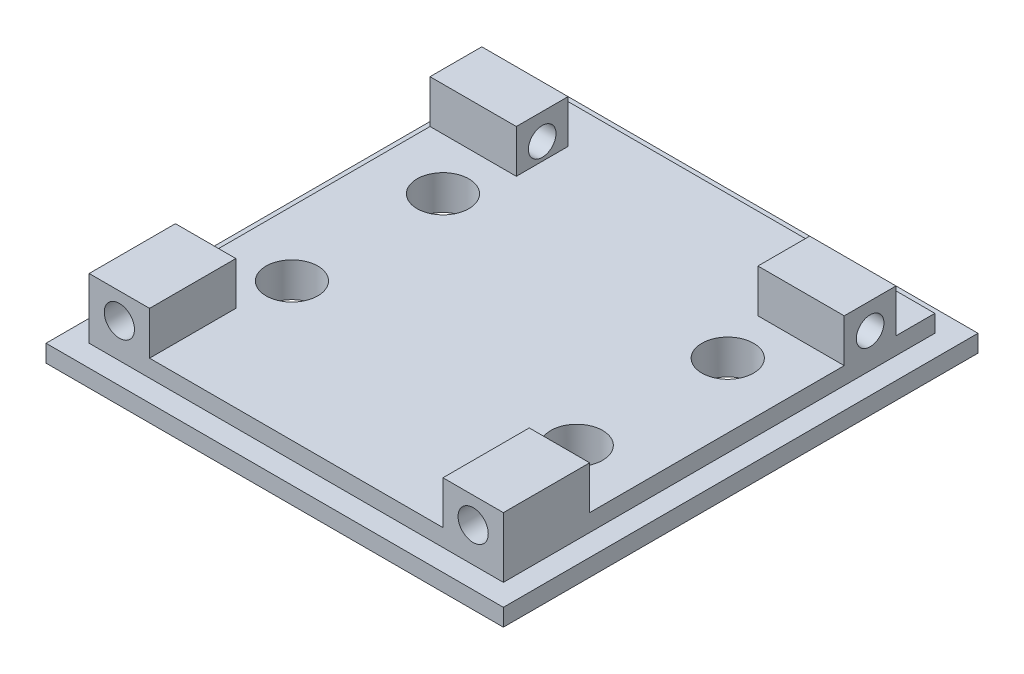
SolidWorks part; units mm, degrees
ref_plane "Front Plane" through (0, 0, 0) normal (0, 0, 1) x (1, 0, 0)
ref_plane "Top Plane" through (0, 0, 0) normal (0, 1, 0) x (1, 0, 0)
ref_plane "Right Plane" through (0, 0, 0) normal (1, 0, 0) x (0, 0, -1)
sketch "Sketch1" plane through (0, 0, 0) normal (0, 1, 0) x (1, 0, 0)
  line L1 (26.5, -27.5) -> (-26.5, -27.5)
  line L2 (26.5, -27.5) -> (26.5, 27.5)
  line L3 (26.5, 27.5) -> (-26.5, 27.5)
  line L4 (-26.5, -27.5) -> (-26.5, 27.5)
  line L5 (26.5, -27.5) -> (-26.5, 27.5) construction
  line L6 (26.5, 27.5) -> (-26.5, -27.5) construction
  point P0 (0, 0)
  dimension "D1" = 55
  dimension "D2" = 53
extrude "Top" add sketch "Sketch1" along normal blind 2
sketch "Sketch2" plane through (0, 2, 0) normal (0, 1, 0) x (1, 0, 0)
  line L0 (26.5, 27.5) -> (-26.5, 27.5) construction
  line L1 (24, -25) -> (-24, -25)
  line L2 (24, -25) -> (24, 25)
  line L3 (24, 25) -> (-24, 25)
  line L4 (-24, -25) -> (-24, 25)
  line L5 (24, -25) -> (-24, 25) construction
  line L6 (24, 25) -> (-24, -25) construction
  line L7 (-26.5, 27.5) -> (-26.5, -27.5) construction
  point P0 (0, 0)
  dimension "D1" = 2.5
  dimension "D2" = 2.5
extrude "Inside Lip" add sketch "Sketch2" along normal blind 2
sketch "Sketch3" plane through (0, 4, 0) normal (0, 1, 0) x (1, 0, 0)
  line L0 (0, -25) -> (0, 25) construction
  line L1 (-24, -25) -> (-17, -25)
  line L2 (-24, -25) -> (-24, -15)
  line L3 (-24, -15) -> (-17, -15)
  line L4 (-17, -25) -> (-17, -15)
  line L5 (-24, -25) -> (24, -25) construction
  line L6 (24, 25) -> (-24, 25) construction
  line L7 (17, -25) -> (17, -15)
  line L8 (24, -15) -> (17, -15)
  line L9 (24, -25) -> (24, -15)
  line L10 (24, -25) -> (17, -25)
  line L11 (24, -25) -> (24, 25) construction
  line L12 (24, 20.5) -> (14, 20.5)
  line L13 (24, 20.5) -> (24, 14.5)
  line L14 (24, 14.5) -> (14, 14.5)
  line L15 (14, 20.5) -> (14, 14.5)
  line L16 (24, 17.5) -> (14, 17.5) construction
  line L17 (-24, 17.5) -> (-14, 17.5) construction
  line L18 (-14, 20.5) -> (-14, 14.5)
  line L19 (-24, 14.5) -> (-14, 14.5)
  line L20 (-24, 20.5) -> (-24, 14.5)
  line L21 (-24, 20.5) -> (-14, 20.5)
  dimension "D1" = 7
  dimension "D2" = 10
  dimension "D3" = 10
  dimension "D4" = 6
  dimension "D5" = 45
extrude "Screw Posts" add sketch "Sketch3" along normal blind 5
sketch "Sketch4" plane through (0, 0, 25) normal (0, 0, 1) x (1, 0, 0)
  line L0 (-24, 2) -> (24, 2) construction
  line L1 (-24, 9) -> (-24, 2) construction
  line L2 (0, 0) -> (0, 12.4771) construction
  circle A0 centre (-20.5, 6) radius 1.75
  circle A1 centre (20.5, 6) radius 1.75
  dimension "D1" = 3.5
  dimension "D2" = 4
  dimension "D3" = 3.5
extrude "Front Screw Holes" cut sketch "Sketch4" against normal up to surface (10 mm away) up to face at (20.5, 6.5, 15)
sketch "Sketch5" plane through (24, 0, 0) normal (1, 0, 0) x (0, 0, -1)
  line L0 (-25, 2) -> (25, 2) construction
  line L1 (17.5, 9) -> (17.5, 2) construction
  line L2 (14.5, 9) -> (20.5, 9) construction
  circle A0 centre (17.5, 6) radius 1.6
  dimension "D1" = 3.2
  dimension "D2" = 4
extrude "Back Screw Holes" cut sketch "Sketch5" against normal up to surface (48 mm away)
sketch "Sketch6" plane through (0, 4, 0) normal (0, 1, 0) x (1, 0, 0)
  line L0 (-24, 14.5) -> (-24, -15) construction
  line L1 (-17, -25) -> (17, -25) construction
  line L2 (-14, 20.5) -> (-24, 20.5) construction
  line L3 (0, -23.2933) -> (0, 25) construction
  line L4 (24, 25) -> (-24, 25) construction
  line L5 (-14, 20.5) -> (-24, 20.5) construction
  circle A0 centre (-16.5, -9) radius 3
  circle A1 centre (-16.5, 8.5) radius 3
  circle A2 centre (16.5, -9) radius 3
  circle A3 centre (16.5, 8.5) radius 3
  point P8 (-19, 20.5)
  dimension "D1" = 7.5
  dimension "D2" = 6
  dimension "D3" = 16
  dimension "D4" = 12
extrude "Cut-Extrude3" cut sketch "Sketch6" against normal up to surface (4 mm away) up to face at (0, 0, 0)
